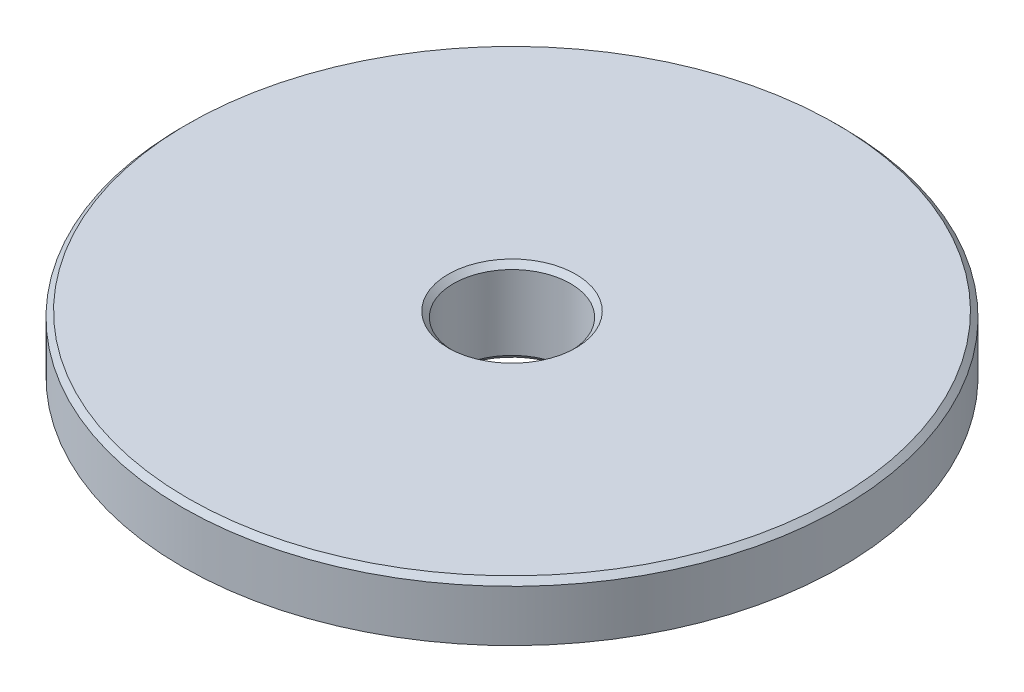
SolidWorks part; units mm, degrees
ref_plane "Front Plane" through (0, 0, 0) normal (0, 0, 1) x (1, 0, 0)
ref_plane "Top Plane" through (0, 0, 0) normal (0, 1, 0) x (1, 0, 0)
ref_plane "Right Plane" through (0, 0, 0) normal (1, 0, 0) x (0, 0, -1)
sketch "Sketch2" plane through (0, 0, 0) normal (0, 0, 1) x (1, 0, 0)
  line L0 (0, 0) -> (0, 4.7625)
  line L1 (0, 4.7625) -> (18.4547, 4.7625)
  line L2 (18.4547, 4.7625) -> (18.4547, 1.5875)
  line L3 (18.4547, 1.5875) -> (15.2797, 1.5875)
  line L4 (15.0813, 1.3891) -> (15.0813, 0)
  line L5 (15.0813, 0) -> (0, 0)
  arc A0 (15.2797, 1.5875) -> (15.0813, 1.3891) centre (15.0813, 1.5875) ccw
  dimension "D4" = 0.3969
  dimension "D1" = 15.0813
  dimension "D2" = 1.5875
  dimension "D3" = 3.175
  dimension "D5" = 3.175
revolve "Revolve1" add sketch "Sketch2" angle 360 about L0
sketch "Sketch3" plane through (0, 0, 0) normal (0, -1, 0) x (-1, 0, 0)
  circle A0 centre (0, 0) radius 3.275
  dimension "D1" = 6.55
extrude "Cut-Extrude1" cut sketch "Sketch3" against normal through all
chamfer "Chamfer1" distance 0.3 angle 45 4 edges at (0, 4.7625, -3.275) (0, 0, -3.275) (0, 0, -15.0813) (0, 4.7625, -18.4547)
